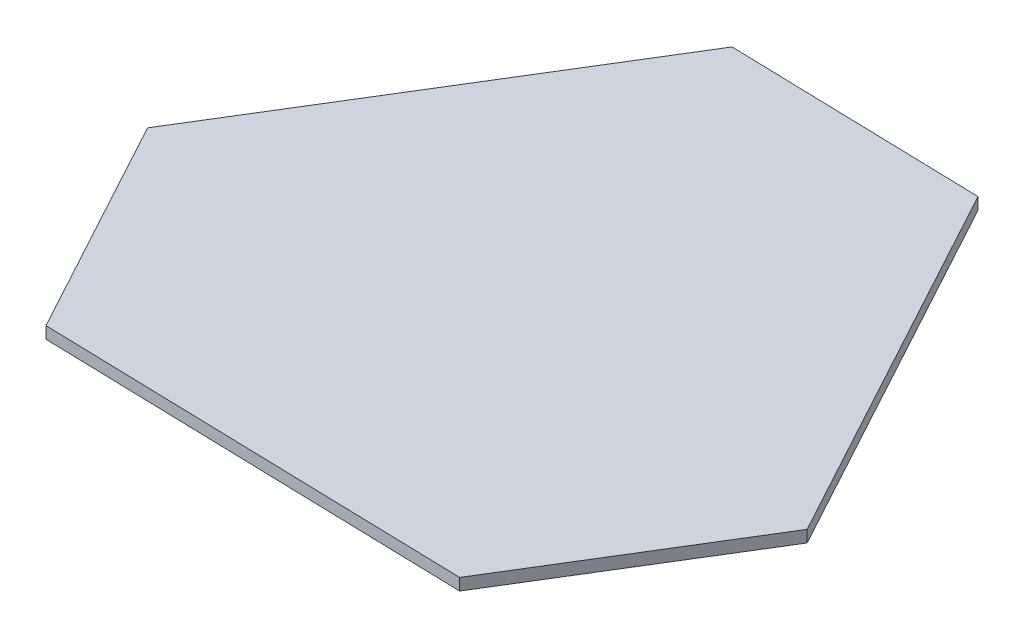
SolidWorks part; units mm, degrees
material "Acrylic (Medium-high impact)"
ref_plane "前视基准面" through (0, 0, 0) normal (0, 0, 1) x (1, 0, 0)
ref_plane "上视基准面" through (0, 0, 0) normal (0, 1, 0) x (1, 0, 0)
ref_plane "右视基准面" through (0, 0, 0) normal (1, 0, 0) x (0, 0, -1)
sketch "Sketch1" plane through (0, 0, 0) normal (0, 1, 0) x (1, 0, 0)
  line L1 (48.2875, 121.6289) -> (-58.675, 124.4611)
  line L2 (-58.675, 124.4611) -> (-152.7695, -28.9867)
  line L3 (-152.7695, -28.9867) -> (-101.741, -123.035)
  line L4 (-101.741, -123.035) -> (78.1959, -127.7994)
  line L5 (78.1959, -127.7994) -> (134.1299, -36.5832)
  line L6 (134.1299, -36.5832) -> (48.2875, 121.6289)
  dimension "D1" = 180
  dimension "D2" = 107
  dimension "D3" = 179.9369
extrude "Boss-Extrude1" add sketch "Sketch1" along normal blind 5
